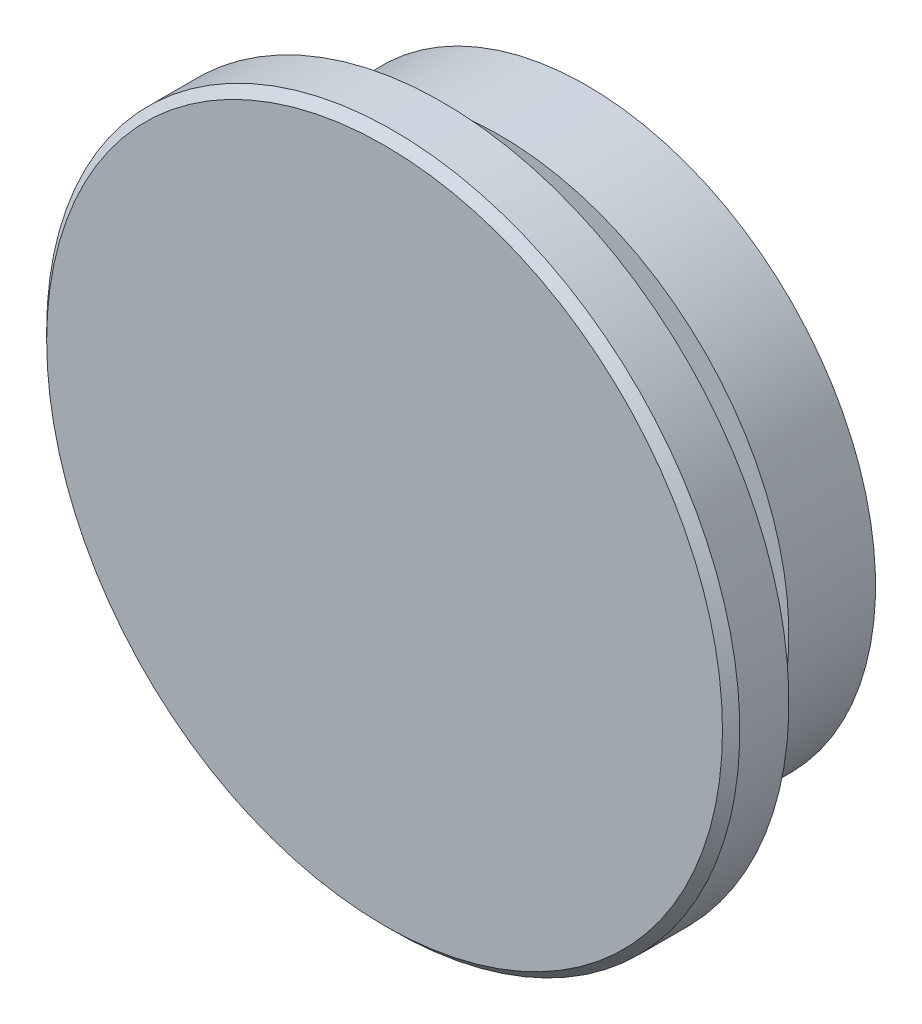
SolidWorks part; units mm, degrees
ref_plane "Спереди" through (0, 0, 0) normal (0, 0, 1) x (1, 0, 0)
ref_plane "Сверху" through (0, 0, 0) normal (0, 1, 0) x (1, 0, 0)
ref_plane "Справа" through (0, 0, 0) normal (1, 0, 0) x (0, 0, -1)
sketch "Эскиз2" plane through (0, 0, 0) normal (0, 1, 0) x (1, 0, 0)
  line L0 (0, 0) -> (-11.7, 0)
  line L1 (-12, 0.3) -> (-12, 2)
  line L2 (-12, 2) -> (-9, 2)
  line L3 (-9, 2) -> (-9, 4)
  line L4 (-9, 4) -> (-10, 4)
  line L5 (-10, 4) -> (-10, 7)
  line L6 (-10, 7) -> (-7.5, 7)
  line L7 (-7.5, 7) -> (-7.5, 5.5)
  line L8 (-7.5, 5.5) -> (0, 5.5)
  line L9 (0, 5.5) -> (0, 0)
  line L10 (-11.7, 0) -> (-12, 0.3)
  point P1 (-12, 0)
  dimension "D1" = 12
  dimension "D2" = 2
  dimension "D3" = 2
  dimension "D4" = 3
  dimension "D5" = 10
  dimension "D6" = 2.5
  dimension "D7" = 1.5
  dimension "D8" = 9
revolve "Повернуть1" add sketch "Эскиз2" angle 360 about L9
